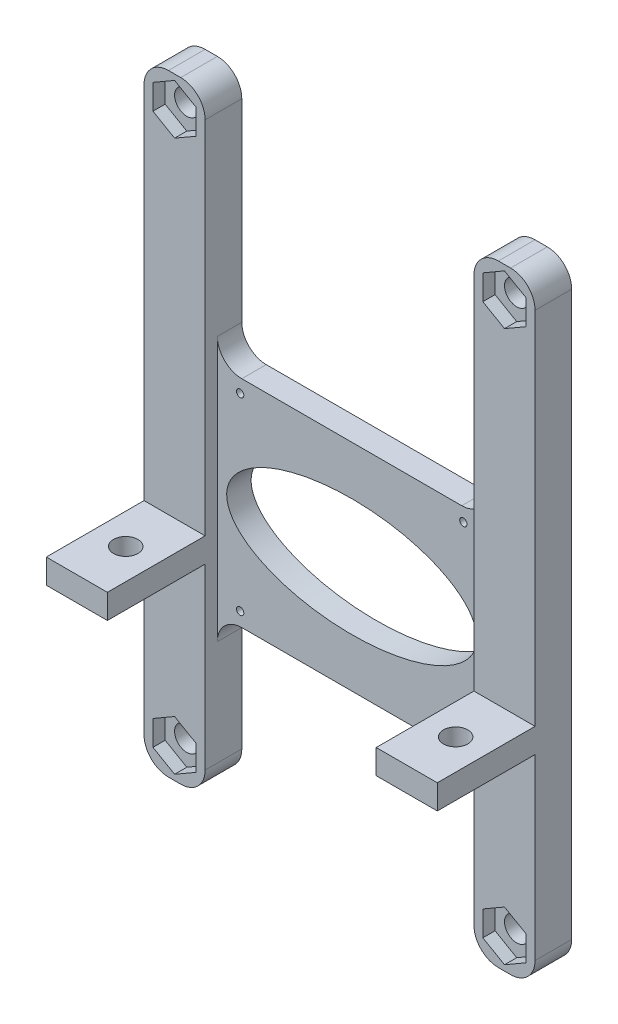
SolidWorks part; units mm, degrees
ref_plane "Front Plane" through (0, 0, 0) normal (0, 0, 1) x (1, 0, 0)
ref_plane "Top Plane" through (0, 0, 0) normal (0, 1, 0) x (1, 0, 0)
ref_plane "Right Plane" through (0, 0, 0) normal (1, 0, 0) x (0, 0, -1)
sketch "Sketch1" plane through (0, 0, 0) normal (0, 0, 1) x (1, 0, 0)
  line L0 (-29, -36) -> (29, -36) construction
  line L1 (-29, -36) -> (-29, 13) construction
  line L2 (29, -36) -> (29, 13) construction
  line L3 (-29, 13) -> (29, 13) construction
  line L4 (29, -36) -> (-29, 13) construction
  line L5 (-29, -36) -> (29, 13) construction
  line L6 (-50.8, -79.5094) -> (50.8, -79.5094) construction
  line L7 (-50.8, -79.5094) -> (-50.8, 79.5094)
  line L8 (50.8, -79.5094) -> (50.8, 79.5094)
  line L9 (-50.8, 79.5094) -> (50.8, 79.5094) construction
  line L10 (-50.8, -79.5094) -> (50.8, 79.5094) construction
  line L11 (50.8, -79.5094) -> (-50.8, 79.5094) construction
  line L12 (-34.925, 16.5) -> (34.925, 16.5)
  line L13 (-50.8, 0) -> (50.8, 0) construction
  line L15 (-50.8, 68) -> (50.8, 68) construction
  line L18 (-50.8, -68) -> (50.8, -68) construction
  line L21 (0, 68) -> (0, -68) construction
  line L22 (-50.8, 79.5094) -> (-34.925, 79.5094)
  line L23 (-34.925, 79.5094) -> (-34.925, 16.5)
  line L24 (50.8, 79.5094) -> (34.925, 79.5094)
  line L25 (34.925, 79.5094) -> (34.925, 16.5)
  line L26 (-34.925, -39.5) -> (-34.925, -79.5094)
  line L27 (-34.925, -79.5094) -> (-50.8, -79.5094)
  line L28 (-34.925, -39.5) -> (34.925, -39.5)
  line L29 (34.925, -39.5) -> (34.925, -79.5094)
  line L30 (34.925, -79.5094) -> (50.8, -79.5094)
  line L31 (32.5, -39.5) -> (-32.5, -39.5) construction
  line L32 (32.5, -39.5) -> (32.5, 16.5) construction
  line L33 (-32.5, -39.5) -> (-32.5, 16.5) construction
  line L34 (32.5, 16.5) -> (-32.5, 16.5) construction
  line L35 (32.5, -39.5) -> (-32.5, 16.5) construction
  line L36 (-32.5, -39.5) -> (32.5, 16.5) construction
  circle A0 centre (29, 13) radius 0.95
  circle A1 centre (29, -36) radius 0.95
  circle A2 centre (-29, -36) radius 0.95
  circle A3 centre (-29, 13) radius 0.95
  circle A10 centre (-42.8625, 71.5719) radius 3.175
  circle A11 centre (42.8625, 71.5719) radius 3.175
  circle A12 centre (-42.8625, -71.5719) radius 3.175
  circle A13 centre (42.8625, -71.5719) radius 3.175
  ellipse E0 centre (0, -11.5) end of major axis (32.5, -11.5) minor radius 15.3
  point P1 (0, 0)
  point P2 (0, 0)
  point P21 (0, 0)
  point P28 (0, -11.5)
  point P35 (0, 16.5)
  point P43 (0, -11.5)
  point P44 (0, 0)
  point P54 (-50.8, 0)
  point P55 (0, 0)
  point P56 (0, -39.5)
  dimension "D1" = 1.9
  dimension "D7" = 3.5719
  dimension "D9" = 7.9375
  dimension "D12" = 6.35
  dimension "D2" = 58
  dimension "D3" = 49
  dimension "D4" = 136
  dimension "D5" = 101.6
  dimension "D6" = 15.875
  dimension "D8" = 7.9375
  dimension "D10" = 32
  dimension "D11" = 3.5719
  dimension "D13" = 7.9375
  dimension "D14" = 12.7
  dimension "D15" = 65
  dimension "D16" = 56
  dimension "D17" = 15.875
extrude "Boss-Extrude1" add sketch "Sketch1" along normal blind 6.35
sketch "Sketch2" plane through (0, 0, 6.35) normal (0, 0, 1) x (1, 0, 0)
  line L0 (-50.8, 79.5094) -> (-50.8, -79.5094)
  line L1 (-50.8, 79.5094) -> (-34.925, 79.5094)
  line L2 (-50.8, -79.5094) -> (-34.925, -79.5094)
  line L3 (-34.925, 79.5094) -> (-34.925, -79.5094) construction
  line L4 (0, 38.2822) -> (0, -62.9404) construction
  line L8 (-34.925, -79.5094) -> (-34.925, 79.5094)
  line L16 (34.925, 79.5094) -> (34.925, -79.5094) construction
  line L17 (-48.4875, 68.3243) -> (-42.8625, 65.0767)
  line L18 (-42.8625, 65.0767) -> (-37.2375, 68.3243)
  line L19 (-37.2375, 68.3243) -> (-37.2375, 74.8195)
  line L20 (-37.2375, 74.8195) -> (-42.8625, 78.0671)
  line L21 (-42.8625, 78.0671) -> (-48.4875, 74.8195)
  line L22 (-48.4875, 74.8195) -> (-48.4875, 68.3243)
  line L23 (-37.2375, -68.3243) -> (-42.8625, -65.0767)
  line L24 (-42.8625, -65.0767) -> (-48.4875, -68.3243)
  line L25 (-48.4875, -68.3243) -> (-48.4875, -74.8195)
  line L26 (-48.4875, -74.8195) -> (-42.8625, -78.0671)
  line L27 (-42.8625, -78.0671) -> (-37.2375, -74.8195)
  line L28 (-37.2375, -74.8195) -> (-37.2375, -68.3243)
  line L29 (37.2375, -74.8195) -> (37.2375, -68.3243)
  line L30 (42.8625, -78.0671) -> (37.2375, -74.8195)
  line L31 (48.4875, -74.8195) -> (42.8625, -78.0671)
  line L32 (48.4875, -68.3243) -> (48.4875, -74.8195)
  line L33 (42.8625, -65.0767) -> (48.4875, -68.3243)
  line L34 (37.2375, -68.3243) -> (42.8625, -65.0767)
  line L35 (48.4875, 74.8195) -> (48.4875, 68.3243)
  line L36 (42.8625, 78.0671) -> (48.4875, 74.8195)
  line L37 (37.2375, 74.8195) -> (42.8625, 78.0671)
  line L38 (37.2375, 68.3243) -> (37.2375, 74.8195)
  line L39 (42.8625, 65.0767) -> (37.2375, 68.3243)
  line L40 (48.4875, 68.3243) -> (42.8625, 65.0767)
  line L41 (34.925, -79.5094) -> (34.925, 79.5094)
  line L45 (50.8, -79.5094) -> (34.925, -79.5094)
  line L46 (50.8, 79.5094) -> (34.925, 79.5094)
  line L47 (50.8, 79.5094) -> (50.8, -79.5094)
  circle A0 centre (-42.8625, 71.5719) radius 5.625 construction
  circle A1 centre (-42.8625, -71.5719) radius 5.625 construction
  circle A2 centre (42.8625, -71.5719) radius 5.625 construction
  circle A3 centre (42.8625, 71.5719) radius 5.625 construction
  dimension "D1" = 15.875
  dimension "D2" = 11.25
extrude "Boss-Extrude2" add sketch "Sketch2" along normal blind 3.175
sketch "Sketch3" plane through (0, 0, 9.525) normal (0, 0, 1) x (1, 0, 0)
  line L0 (-34.925, -26.8) -> (-34.925, -20.45)
  line L1 (-34.925, -26.8) -> (-50.8, -26.8)
  line L2 (-34.925, -20.45) -> (-50.8, -20.45)
  line L3 (-50.8, -26.8) -> (-50.8, -20.45)
  line L5 (-34.925, -39.5) -> (34.925, -39.5) construction
  line L6 (-34.925, -79.5094) -> (-34.925, 79.5094) construction
  line L8 (-50.8, 79.5094) -> (-50.8, -79.5094) construction
  line L9 (0, 0) -> (0, -33.67) construction
  line L10 (50.8, -26.8) -> (50.8, -20.45)
  line L11 (34.925, -20.45) -> (50.8, -20.45)
  line L12 (34.925, -26.8) -> (50.8, -26.8)
  line L13 (34.925, -26.8) -> (34.925, -20.45)
  dimension "D1" = 6.35
  dimension "D2" = 19.05
extrude "Boss-Extrude3" add sketch "Sketch3" along normal blind 25.4
sketch "Sketch4" plane through (0, -26.8, 0) normal (0, 1, 0) x (1, 0, 0)
  line L0 (-42.8625, -34.925) -> (-42.8625, -9.525) construction
  line L1 (-34.925, -34.925) -> (-50.8, -34.925) construction
  line L3 (0, 0) -> (0, -31.3873) construction
  line L4 (-50.8, -9.525) -> (-34.925, -9.525) construction
  circle A0 centre (-42.8625, -22.225) radius 3.175
  circle A1 centre (42.8625, -22.225) radius 3.175
  dimension "D1" = 6.35
extrude "Cut-Extrude1" cut sketch "Sketch4" along normal through all
fillet "Fillet2" radius 6.35 12 edges at (34.925, -39.5, 3.175) (-34.925, -39.5, 3.175) (-50.8, -79.5094, 4.7625) (-34.925, -79.5094, 4.7625) (34.925, -79.5094, 4.7625) (50.8, -79.5094, 4.7625) (50.8, 79.5094, 4.7625) (34.925, 79.5094, 4.7625) (34.925, 16.5, 3.175) (-34.925, 16.5, 3.175) (-34.925, 79.5094, 4.7625) (-50.8, 79.5094, 4.7625)
